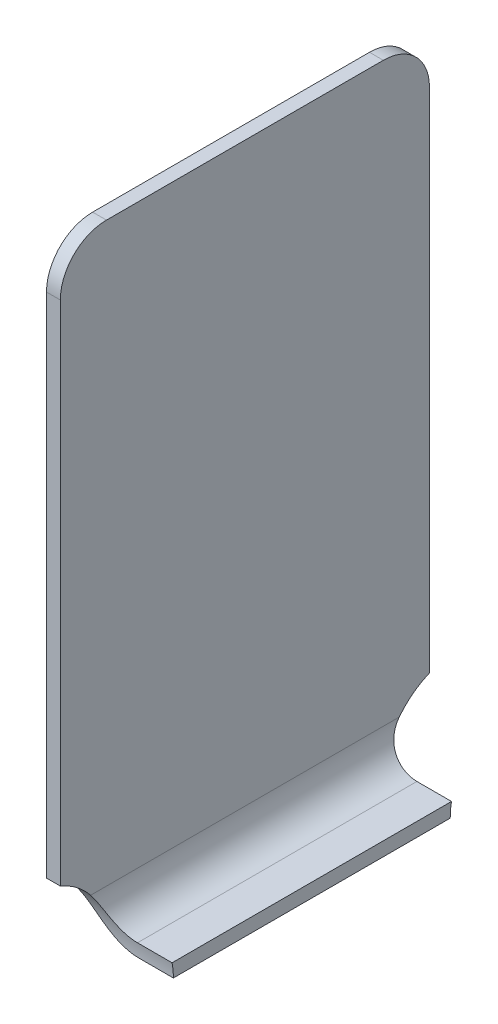
SolidWorks part; units mm, degrees
ref_plane "Front Plane" through (0, 0, 0) normal (0, 0, 1) x (1, 0, 0)
ref_plane "Top Plane" through (0, 0, 0) normal (0, 1, 0) x (1, 0, 0)
ref_plane "Right Plane" through (0, 0, 0) normal (1, 0, 0) x (0, 0, -1)
sketch "Sketch1" plane through (0, 0, 0) normal (0, 0, 1) x (1, 0, 0)
  line L0 (0, 0) -> (-19.05, 0)
  line L1 (-44.45, 25.4) -> (-44.45, 342.9)
  arc A0 (-19.05, 0) -> (-44.45, 25.4) centre (-19.05, 25.4) cw
extrude "Extrude-Thin1" add sketch "Sketch1" along normal mid plane 203.2 thin
fillet "Fillet1" radius 25.4 1 edges at (-40.64, 342.9, 101.6)
fillet "Fillet2" radius 25.4 1 edges at (-40.64, 342.9, -101.6)
sketch3d "3DSketch1"
  point P0 (0, 3.4181, 29.6445)
sketch3d "3DSketch2"
  point P0 (0, 4.0614, -8.6423)
ref_plane "Front Plane on End" through (0, 0, 0) normal (1, 0, 0) x (0, 0, -1)
sketch "Sketch2" plane through (0, 0, 0) normal (1, 0, 0) x (0, 0, -1)
  line L0 (-101.6, 0) -> (-76.2, 0)
  line L1 (-101.6, 0) -> (101.6, 0) construction
  line L2 (-101.6, 0) -> (-101.6, 38.1)
  line L3 (101.6, 0) -> (101.6, 38.1)
  line L4 (101.6, 0) -> (76.2, 0)
  arc A0 (-76.2, 0) -> (-101.6, 38.1) centre (-117.475, 0) ccw
  arc A1 (76.2, 0) -> (101.6, 38.1) centre (117.475, 0) cw
extrude "Cut-Extrude1" cut sketch "Sketch2" against normal blind 67.818 and the other way blind 15.494
